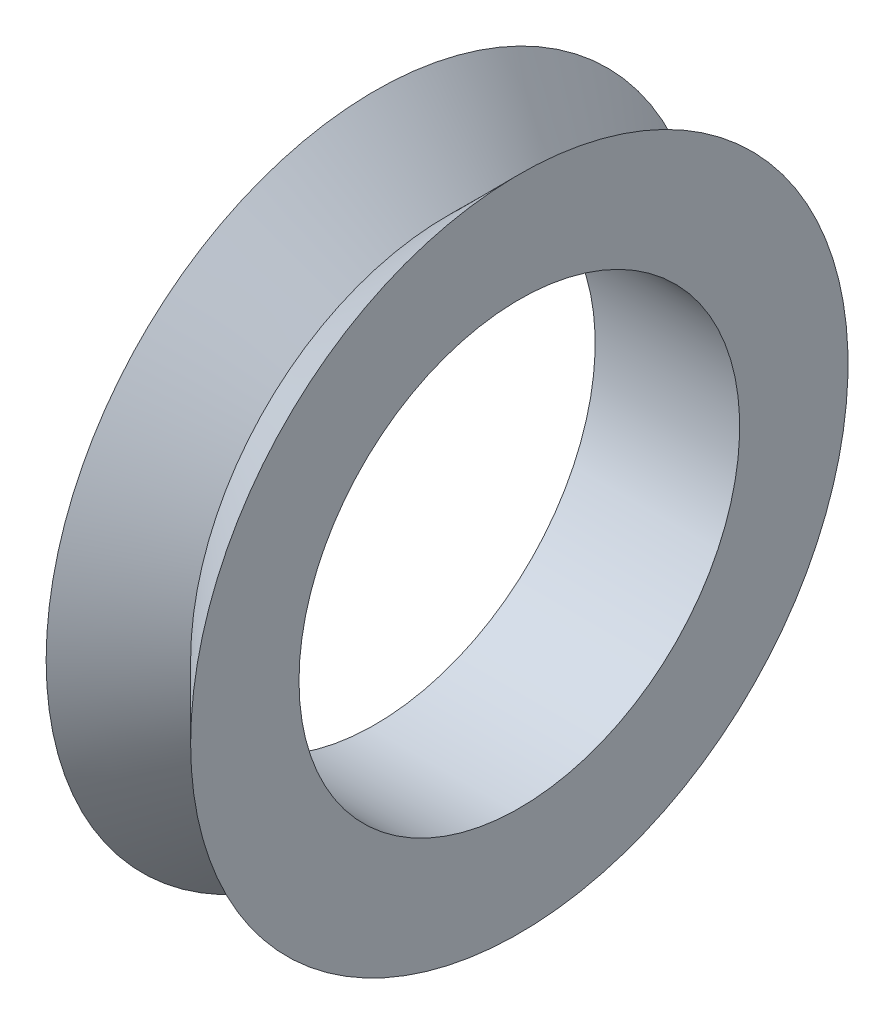
SolidWorks part; units mm, degrees
ref_plane "Front Plane" through (0, 0, 0) normal (0, 0, 1) x (1, 0, 0)
ref_plane "Top Plane" through (0, 0, 0) normal (0, 1, 0) x (1, 0, 0)
ref_plane "Right Plane" through (0, 0, 0) normal (1, 0, 0) x (0, 0, -1)
ref_axis "Axis1" through (-6.9241, 0, 0) along (1, 0, 0)
sketch "Sketch5" plane through (0, 0, 0) normal (0, 0, 1) x (1, 0, 0)
  line L0 (0, 0) -> (0, 6.1) construction
  line L1 (-2, 6.1) -> (2, 6.1)
  line L2 (-2, 6.1) -> (-2, 9.1)
  line L3 (-2, 9.1) -> (0, 7.1)
  line L4 (2, 6.1) -> (2, 9.1)
  line L5 (2, 9.1) -> (0, 7.1)
  point P6 (0, 6.1)
  point P9 (0, 11.1244)
  dimension "D1" = 6.1
  dimension "D2" = 4
  dimension "D3" = 3
  dimension "D4" = 2
revolve "Revolve4" add sketch "Sketch5" angle 360 about axis through (-6.9241, 0, 0) along (1, 0, 0)
